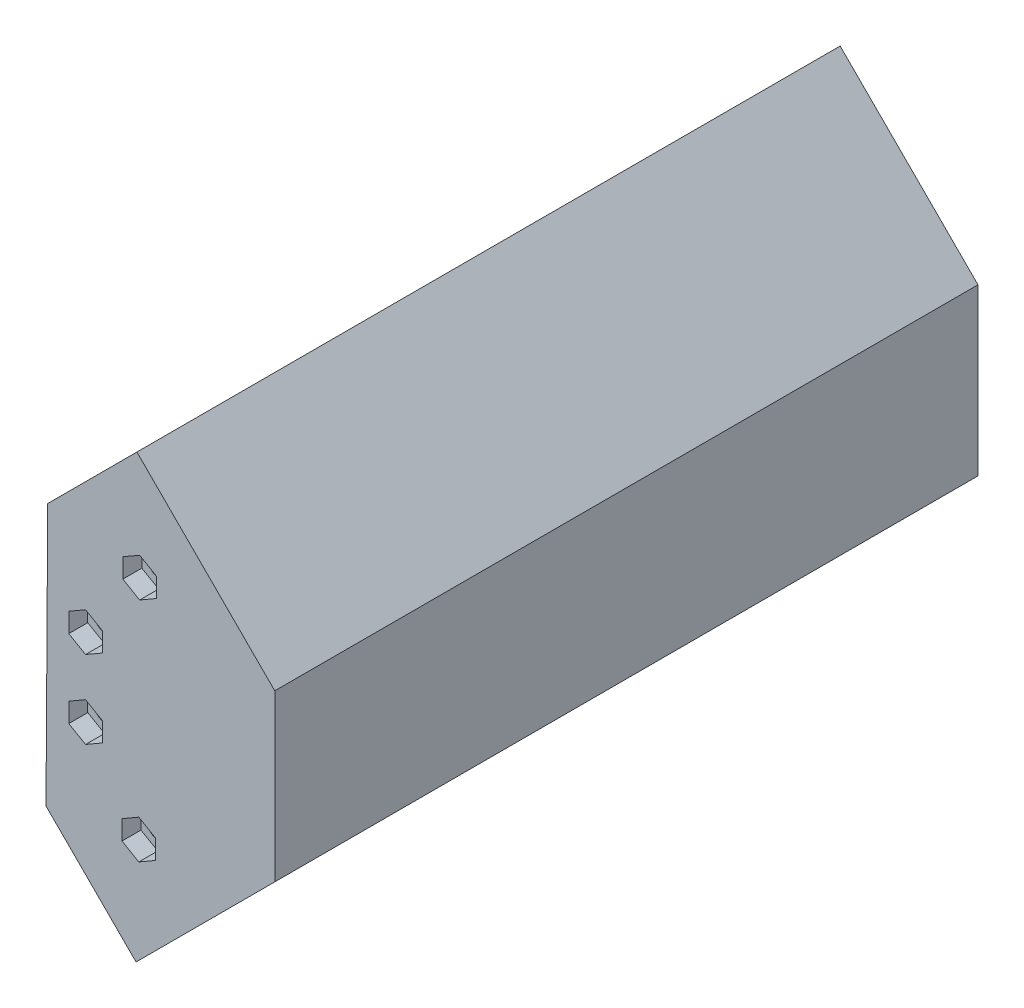
SolidWorks part; units mm, degrees
ref_plane "Front Plane" through (0, 0, 0) normal (0, 0, 1) x (1, 0, 0)
ref_plane "Top Plane" through (0, 0, 0) normal (0, 1, 0) x (1, 0, 0)
ref_plane "Right Plane" through (0, 0, 0) normal (1, 0, 0) x (0, 0, -1)
sketch "Sketch1" plane through (0, 0, 0) normal (0, 0, 1) x (1, 0, 0)
  line L0 (0, 17) -> (0, -17)
  line L1 (0, -17) -> (-10, -27)
  line L2 (-10, -27) -> (-20, -27) construction
  line L3 (-20, -27) -> (-20, 27) construction
  line L4 (-20, 27) -> (-10, 27) construction
  line L5 (-10, 27) -> (0, 17)
  line L6 (-47, -27) -> (-28.5, -45.5)
  line L7 (0, -17) -> (-155, -172) construction
  line L8 (-28.5, -45.5) -> (-10, -27)
  line L9 (-47, -27) -> (-20, -27) construction
  line L10 (-46.6464, 27) -> (-28.3232, 45.3232)
  line L11 (-155, 172) -> (0, 17) construction
  line L12 (-28.3232, 45.3232) -> (-10, 27)
  line L13 (-20, 27) -> (-46.6464, 27) construction
  line L14 (-46.6464, 27) -> (-47, -27)
  circle A0 centre (-10, -8) radius 2
  circle A1 centre (-10, 8) radius 2
  dimension "D1" = 4
  dimension "D2" = 4
extrude "Boss-Extrude1" add sketch "Sketch1" along normal blind 6
sketch "Sketch2" plane through (0, 0, 6) normal (0, 0, 1) x (1, 0, 0)
  line L1 (-10, 11.9837) -> (-13.45, 9.9919)
  line L2 (-13.45, 9.9919) -> (-13.45, 6.0081)
  line L3 (-13.45, 6.0081) -> (-10, 4.0163)
  line L4 (-10, 4.0163) -> (-6.55, 6.0081)
  line L5 (-6.55, 6.0081) -> (-6.55, 9.9919)
  line L6 (-6.55, 9.9919) -> (-10, 11.9837)
  line L7 (-10, -4.0163) -> (-13.45, -6.0081)
  line L8 (-13.45, -6.0081) -> (-13.45, -9.9919)
  line L9 (-13.45, -9.9919) -> (-10, -11.9837)
  line L10 (-10, -11.9837) -> (-6.55, -9.9919)
  line L11 (-6.55, -9.9919) -> (-6.55, -6.0081)
  line L12 (-6.55, -6.0081) -> (-10, -4.0163)
  circle A0 centre (-10, 8) radius 3.45 construction
  circle A1 centre (-10, -8) radius 3.45 construction
  dimension "D1" = 6.9
  dimension "D2" = 6.9
extrude "Cut-Extrude1" cut sketch "Sketch2" against normal blind 3.9
sketch "Sketch3" plane through (0, 0, 6) normal (0, 0, 1) x (1, 0, 0)
  line L0 (-43.818, -23.818) -> (-28.5, -39.136) construction
  line L1 (-28.5, -39.136) -> (-4.5, -15.136)
  line L2 (-4.5, -15.136) -> (-4.5, 15.136)
  line L3 (-4.5, 15.136) -> (-28.3232, 38.9593)
  line L4 (-28.3232, 38.9593) -> (-43.4645, 23.818) construction
  line L5 (-43.818, -23.818) -> (-46.9792, -23.818) construction
  line L6 (0, 17) -> (-28.3232, 45.3232)
  line L7 (-28.3232, 45.3232) -> (-46.6464, 27)
  line L8 (-46.6464, 27) -> (-47, -27)
  line L9 (-47, -27) -> (-28.5, -45.5)
  line L10 (-28.5, -45.5) -> (0, -17)
  line L11 (0, -17) -> (0, 17)
  line L12 (0, 17) -> (-28.3232, 45.3232)
  line L13 (-28.3232, 45.3232) -> (-31.5052, 42.1412)
  line L14 (-46.6464, 27) -> (-46.6673, 23.818) construction
  line L15 (-47, -27) -> (-28.5, -45.5) construction
  line L16 (-28.5, -45.5) -> (0, -17)
  line L17 (0, -17) -> (0, 17)
  line L18 (-43.4645, 23.818) -> (-46.6673, 23.818) construction
  line L19 (-46.6673, 23.818) -> (-46.9792, -23.818) construction
  line L20 (-46.9792, -23.818) -> (-47, -27) construction
  line L21 (-28.5, -39.136) -> (-31.682, -42.318)
  line L22 (-31.682, -42.318) -> (-28.5, -45.5)
  line L23 (-28.3232, 38.9593) -> (-31.5052, 42.1412)
  line L24 (-31.5052, 42.1412) -> (-46.6464, 27) construction
  line L25 (-28.3232, 45.3232) -> (-46.6464, 27) construction
  dimension "D1" = 0
  dimension "D2" = 4.5
extrude "Boss-Extrude2" add sketch "Sketch3" along normal up to surface (138.4752 mm away)
sketch "Sketch4" plane through (0, 0, 144.4752) normal (0, 0, 1) x (1, 0, 0)
  line L0 (0, 17) -> (0, -17)
  line L1 (0, -17) -> (-28.5, -45.5)
  line L2 (-28.5, -45.5) -> (-47, -27)
  line L3 (-47, -27) -> (-46.6464, 27)
  line L4 (-46.6464, 27) -> (-28.3232, 45.3232)
  line L5 (-28.3232, 45.3232) -> (0, 17)
extrude "Boss-Extrude3" add sketch "Sketch4" against normal blind 8
sketch "Sketch5" plane through (0, 0, 144.4752) normal (0, 0, 1) x (1, 0, 0)
  line L0 (-46.6464, 27) -> (-1.3232, -18.3232) construction
  line L1 (0, -17) -> (-28.5, -45.5) construction
  line L2 (-19.8964, 0.25) -> (-171.75, 152.1036) construction
  line L3 (-46.8232, -27.1768) -> (-1.3232, 18.3232) construction
  line L4 (-28.5, -45.5) -> (-47, -27) construction
  line L5 (-171.75, -152.1036) -> (-19.8964, -0.25) construction
  line L6 (-28.3232, 45.3232) -> (0, 17) construction
  line L10 (-31.682, -42.318) -> (-46.8232, -27.1768) construction
  line L11 (-31.5052, 42.1412) -> (-46.6464, 27) construction
  line L12 (-39.2526, -34.7474) -> (-27.9389, -23.4337) construction
  line L13 (-31.5052, 42.1412) -> (-4.5, 15.136)
  line L14 (-4.5, 15.136) -> (-4.5, -15.136)
  line L15 (-4.5, -15.136) -> (-31.682, -42.318)
  line L16 (-31.5052, 42.1412) -> (-4.5, 15.136) construction
  line L17 (-4.5, 15.136) -> (-4.5, -15.136) construction
  line L18 (-4.5, -15.136) -> (-31.682, -42.318) construction
  line L19 (-39.0758, 34.5706) -> (-27.7621, 23.2569) construction
  line L20 (-46.6464, 27) -> (-47, -27) construction
  circle A0 centre (-27.9389, -23.4337) radius 2
  circle A1 centre (-27.7621, 23.2569) radius 2
  circle A2 centre (-38.8754, -8) radius 2
  circle A3 centre (-38.8754, 8) radius 2
  point P29 (-4.5, 0)
  dimension "D4" = 4
  dimension "D5" = 4
  dimension "D9" = 4
  dimension "D10" = 4
  dimension "D2" = 16
  dimension "D3" = 16
  dimension "D6" = 8
  dimension "D7" = 8
  dimension "D8" = 8
  dimension "D1" = 4.5
extrude "Cut-Extrude2" cut sketch "Sketch5" against normal up to next and the other way through all
sketch "Sketch6" plane through (0, 0, 144.4752) normal (0, 0, 1) x (1, 0, 0)
  line L1 (-27.7621, 27.2406) -> (-31.2121, 25.2488)
  line L2 (-31.2121, 25.2488) -> (-31.2121, 21.2651)
  line L3 (-31.2121, 21.2651) -> (-27.7621, 19.2732)
  line L4 (-27.7621, 19.2732) -> (-24.3121, 21.2651)
  line L5 (-24.3121, 21.2651) -> (-24.3121, 25.2488)
  line L6 (-24.3121, 25.2488) -> (-27.7621, 27.2406)
  line L7 (-38.8754, 11.9837) -> (-42.3254, 9.9919)
  line L8 (-42.3254, 9.9919) -> (-42.3254, 6.0081)
  line L9 (-42.3254, 6.0081) -> (-38.8754, 4.0163)
  line L10 (-38.8754, 4.0163) -> (-35.4254, 6.0081)
  line L11 (-35.4254, 6.0081) -> (-35.4254, 9.9919)
  line L12 (-35.4254, 9.9919) -> (-38.8754, 11.9837)
  line L13 (-38.8754, -4.0163) -> (-42.3254, -6.0081)
  line L14 (-42.3254, -6.0081) -> (-42.3254, -9.9919)
  line L15 (-42.3254, -9.9919) -> (-38.8754, -11.9837)
  line L16 (-38.8754, -11.9837) -> (-35.4254, -9.9919)
  line L17 (-35.4254, -9.9919) -> (-35.4254, -6.0081)
  line L18 (-35.4254, -6.0081) -> (-38.8754, -4.0163)
  line L19 (-27.9389, -19.45) -> (-31.3889, -21.4418)
  line L20 (-31.3889, -21.4418) -> (-31.3889, -25.4255)
  line L21 (-31.3889, -25.4255) -> (-27.9389, -27.4174)
  line L22 (-27.9389, -27.4174) -> (-24.4889, -25.4255)
  line L23 (-24.4889, -25.4255) -> (-24.4889, -21.4418)
  line L24 (-24.4889, -21.4418) -> (-27.9389, -19.45)
  circle A0 centre (-27.7621, 23.2569) radius 3.45 construction
  circle A1 centre (-38.8754, 8) radius 3.45 construction
  circle A2 centre (-38.8754, -8) radius 3.45 construction
  circle A3 centre (-27.9389, -23.4337) radius 3.45 construction
  dimension "D1" = 6.9
  dimension "D2" = 6.9
  dimension "D3" = 6.9
  dimension "D4" = 6.9
extrude "Cut-Extrude3" cut sketch "Sketch6" against normal blind 3.9
